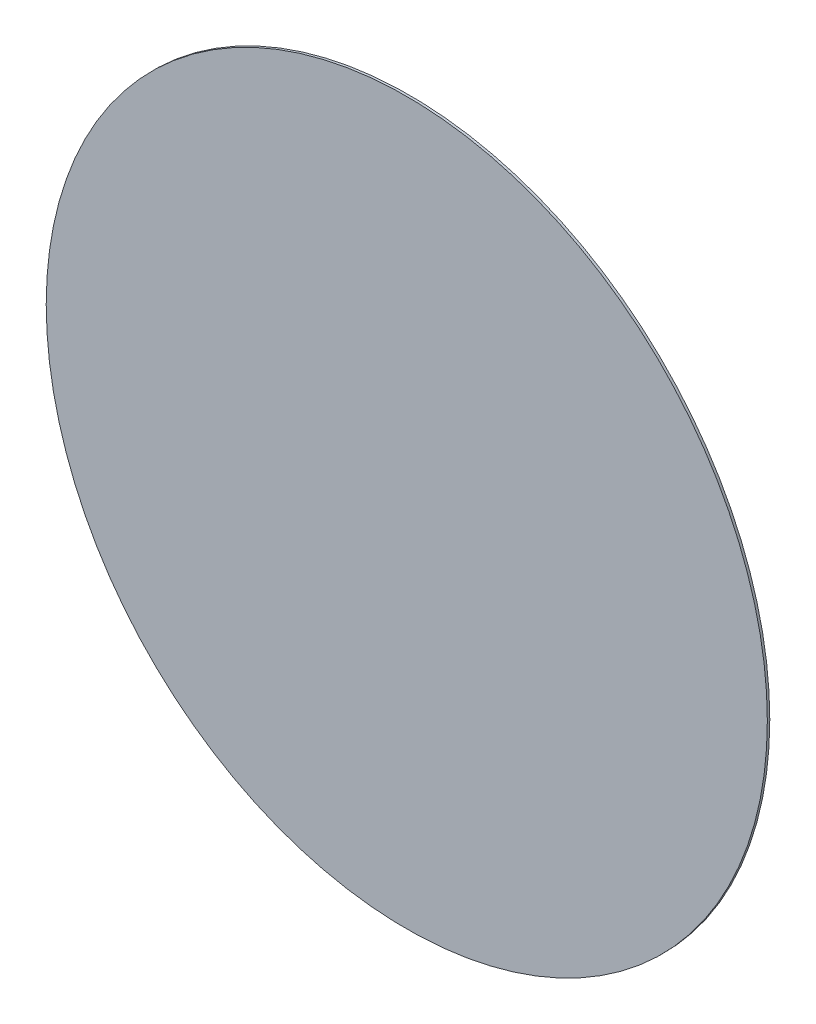
SolidWorks part; units mm, degrees
ref_plane "Front Plane" through (0, 0, 0) normal (0, 0, 1) x (1, 0, 0)
ref_plane "Top Plane" through (0, 0, 0) normal (0, 1, 0) x (1, 0, 0)
ref_plane "Right Plane" through (0, 0, 0) normal (1, 0, 0) x (0, 0, -1)
sketch "CurveSketch" plane through (0, 0, 0) normal (0, 0, 1) x (1, 0, 0)
  circle A0 centre (-3.719, 5.173) radius 1731.719
  dimension "D1" = 1731.719
extrude "CurveBoss" add sketch "CurveSketch" along normal blind 11.731
